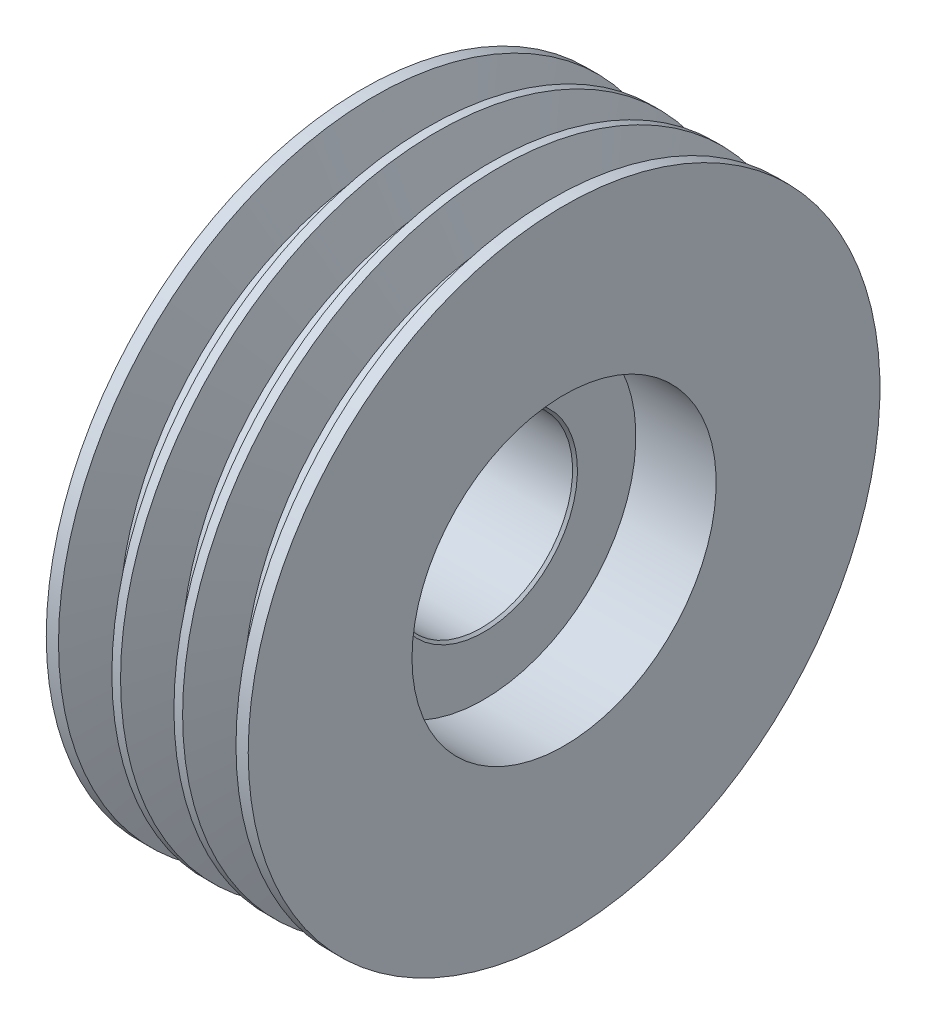
SolidWorks part; units mm, degrees
ref_plane "前视基准面" through (0, 0, 0) normal (0, 0, 1) x (1, 0, 0)
ref_plane "上视基准面" through (0, 0, 0) normal (0, 1, 0) x (1, 0, 0)
ref_plane "右视基准面" through (0, 0, 0) normal (1, 0, 0) x (0, 0, -1)
sketch "草图1" plane through (0, 0, 0) normal (0, 0, 1) x (1, 0, 0)
  line L0 (0, 0) -> (64.8368, 0) construction
  line L1 (0, 37.5) -> (0, 129.8)
  line L2 (0, 129.8) -> (83, 129.8)
  line L3 (83, 129.8) -> (83, 62.5)
  line L4 (83, 62.5) -> (50, 62.5)
  line L5 (50, 62.5) -> (50, 37.5)
  line L6 (50, 37.5) -> (0, 37.5)
  line L7 (5.0325, 129.8) -> (10.8719, 110.7) construction
  line L8 (10.8719, 110.7) -> (21.1281, 110.7) construction
  line L9 (21.1281, 110.7) -> (26.9675, 129.8) construction
  line L10 (0, 125) -> (83, 125) construction
  line L11 (16, 110.7) -> (16, 37.5) construction
  point P17 (6.5, 125)
  point P18 (25.5, 125)
  dimension "d2" = 259.6
  dimension "L" = 50
  dimension "B" = 83
  dimension "d" = 75
  dimension "d1" = 125
  dimension "dd" = 250
  dimension "f" = 16
  dimension "槽轮角" = 34
  dimension "bd" = 19
  dimension "hf" = 14.3
  dimension "ha" = 4.8
revolve "旋转1" add sketch "草图1" angle 360 about L0
sketch "草图2" plane through (0, 0, 0) normal (0, 0, 1) x (1, 0, 0)
  line L0 (21.1281, 110.7) -> (26.9675, 129.8) construction
  line L1 (10.8719, 110.7) -> (21.1281, 110.7) construction
  line L2 (5.0325, 129.8) -> (10.8719, 110.7) construction
  line L3 (21.1281, 110.7) -> (26.9675, 129.8)
  line L4 (10.8719, 110.7) -> (21.1281, 110.7)
  line L5 (5.0325, 129.8) -> (10.8719, 110.7)
  line L6 (5.0325, 129.8) -> (26.9675, 129.8)
  line L7 (0, 0) -> (83, 0) construction
  line L8 (83, -62.5) -> (83, 62.5) construction
revolve "切除-旋转1" cut sketch "草图2" angle 360 about L7
pattern_linear "阵列(线性)1" count 3 spacing 25.5 along (1, 0, 0) of "切除-旋转1"
chamfer "倒角1" distance 1 2 edges at (50, 0, 37.5) (0, 0, 37.5)
sketch "草图4" plane through (0, 0, 0) normal (-1, 0, 0) x (0, 0, 1)
  line L1 (-10, 36.1421) -> (10, 36.1421)
  line L2 (-10, 36.1421) -> (-10, 42.4)
  line L3 (-10, 42.4) -> (10, 42.4)
  line L4 (10, 36.1421) -> (10, 42.4)
  circle A0 centre (0, 0) radius 37.5 construction
  point P6 (5.1, 42.4)
  dimension "键槽高度" = 42.4
  dimension "键槽宽度" = 20
  dimension "t1" = 4.9
extrude "切除-拉伸1" cut sketch "草图4" against normal through all
